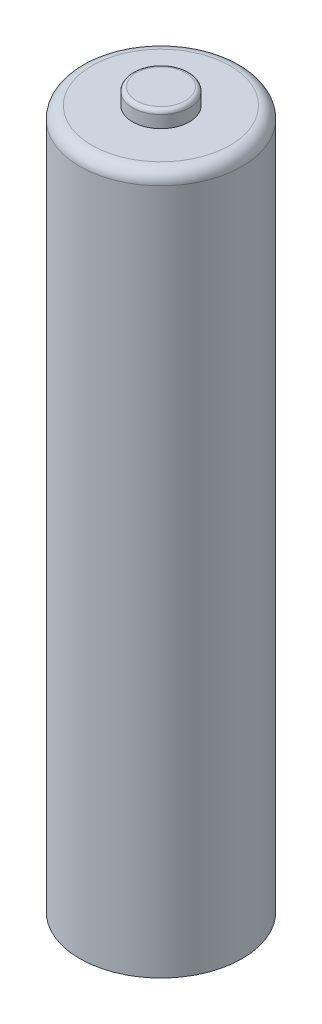
SolidWorks part; units mm, degrees
ref_plane "Front Plane" through (0, 0, 0) normal (0, 0, 1) x (1, 0, 0)
ref_plane "Top Plane" through (0, 0, 0) normal (0, 1, 0) x (1, 0, 0)
ref_plane "Right Plane" through (0, 0, 0) normal (1, 0, 0) x (0, 0, -1)
sketch "Sketch1" plane through (0, 0, 0) normal (0, 0, 1) x (1, 0, 0)
  line L0 (0, 0) -> (0, -53.4264) construction
  line L1 (0, 0) -> (-5, 0)
  line L2 (-5, 0) -> (-5, -43)
  line L4 (0, -43) -> (0, 0)
  line L5 (0, -43) -> (-5, -43)
  dimension "D1" = 10
  dimension "D3" = 43
revolve "Revolve1" add sketch "Sketch1" angle 360 about L0
sketch "Sketch2" plane through (0, 0, 0) normal (0, 0, 1) x (1, 0, 0)
  line L0 (0, 0) -> (0, 11.638) construction
  line L1 (5, 0) -> (-5, 0) construction
  line L2 (0, 1) -> (-1.75, 1)
  line L3 (-1.75, 1) -> (-1.75, 0)
  line L4 (-1.75, 0) -> (0, 0)
  line L5 (0, 0) -> (0, 1)
  dimension "D1" = 3.5
  dimension "D2" = 1
revolve "Revolve2" add sketch "Sketch2" angle 360 about L0
fillet "Fillet1" radius 0.75 1 edges at (0, 0, 5)
fillet "Fillet2" radius 0.25 1 edges at (0, 1, -1.75)
